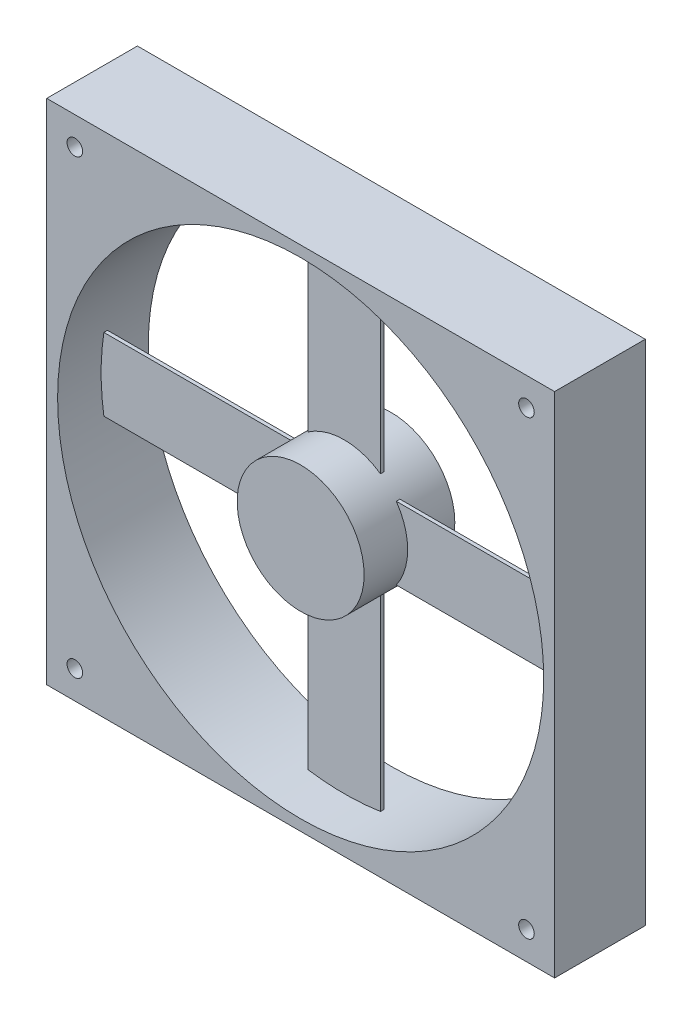
SolidWorks part; units mm, degrees
material "ABS"
ref_plane "Přední rovina" through (0, 0, 0) normal (0, 0, 1) x (1, 0, 0)
ref_plane "Horní rovina" through (0, 0, 0) normal (0, 1, 0) x (1, 0, 0)
ref_plane "Pravá rovina" through (0, 0, 0) normal (1, 0, 0) x (0, 0, -1)
sketch "Skica1" plane through (0, 0, 0) normal (0, 0, 1) x (1, 0, 0)
  line L0 (-70, 70) -> (70, -70) construction
  line L1 (-70, 70) -> (70, 70)
  line L2 (-70, 70) -> (-70, -70)
  line L3 (-70, -70) -> (70, -70)
  line L4 (70, 70) -> (70, -70)
  dimension "D1" = 140
  dimension "D2" = 140
extrude "Přidat vysunutím1" add sketch "Skica1" along normal blind 25
sketch "Skica2" plane through (0, 0, 25) normal (0, 0, 1) x (1, 0, 0)
  line L0 (-62.25, 62.25) -> (62.25, -62.25) construction
  line L1 (0, 0) -> (44.4471, 0) construction
  circle A0 centre (-62.25, 62.25) radius 2.15
  circle A1 centre (-62.25, -62.25) radius 2.15
  circle A2 centre (62.25, -62.25) radius 2.15
  circle A3 centre (62.25, 62.25) radius 2.15
  dimension "D2" = 124.5
  dimension "D3" = 4.3
  dimension "D1" = 45
extrude "Odebrat vysunutím1" cut sketch "Skica2" against normal through all
sketch "Skica3" plane through (0, 0, 25) normal (0, 0, 1) x (1, 0, 0)
  line L0 (70, -70) -> (70, 70) construction
  circle A0 centre (0, 0) radius 67
  circle A1 centre (0, 0) radius 17.5
  dimension "D1" = 3
  dimension "D2" = 35
extrude "Odebrat vysunutím3" cut sketch "Skica3" against normal through all
ref_plane "Rovina1" through (0, 0, 12.5) normal (0, 0, -1) x (-1, 0, 0)
sketch "Skica4" plane through (0, 0, 12.5) normal (0, 0, -1) x (-1, 0, 0)
  line L0 (-10, 66.2495) -> (-10, 14.3614)
  line L1 (10, 66.2495) -> (10, 14.3614)
  line L2 (-66.2495, 10) -> (-14.3614, 10)
  line L3 (-66.2495, -10) -> (-14.3614, -10)
  line L4 (10, 66.2495) -> (-10, -66.2495) construction
  line L5 (-66.2495, 10) -> (66.2495, -10) construction
  line L6 (14.3614, 10) -> (66.2495, 10)
  line L7 (-10, -14.3614) -> (-10, -66.2495)
  line L8 (10, -14.3614) -> (10, -66.2495)
  line L9 (14.3614, -10) -> (66.2495, -10)
  circle A1 centre (0, 0) radius 67 construction
  circle A2 centre (0, 0) radius 17.5 construction
  arc A3 (-14.3614, -10) -> (-10, -14.3614) centre (0, 0) ccw
  arc A4 (-66.2495, 10) -> (-66.2495, -10) centre (0, 0) ccw
  arc A5 (-10, 14.3614) -> (-14.3614, 10) centre (0, 0) ccw
  arc A6 (14.3614, 10) -> (10, 14.3614) centre (0, 0) ccw
  arc A7 (10, -14.3614) -> (14.3614, -10) centre (0, 0) ccw
  arc A8 (10, 66.2495) -> (-10, 66.2495) centre (0, 0) ccw
  arc A9 (66.2495, -10) -> (66.2495, 10) centre (0, 0) ccw
  arc A10 (-10, -66.2495) -> (10, -66.2495) centre (0, 0) ccw
  dimension "D1" = 20
  dimension "D2" = 20
extrude "Přidat vysunutím2" add sketch "Skica4" along normal mid plane 1
